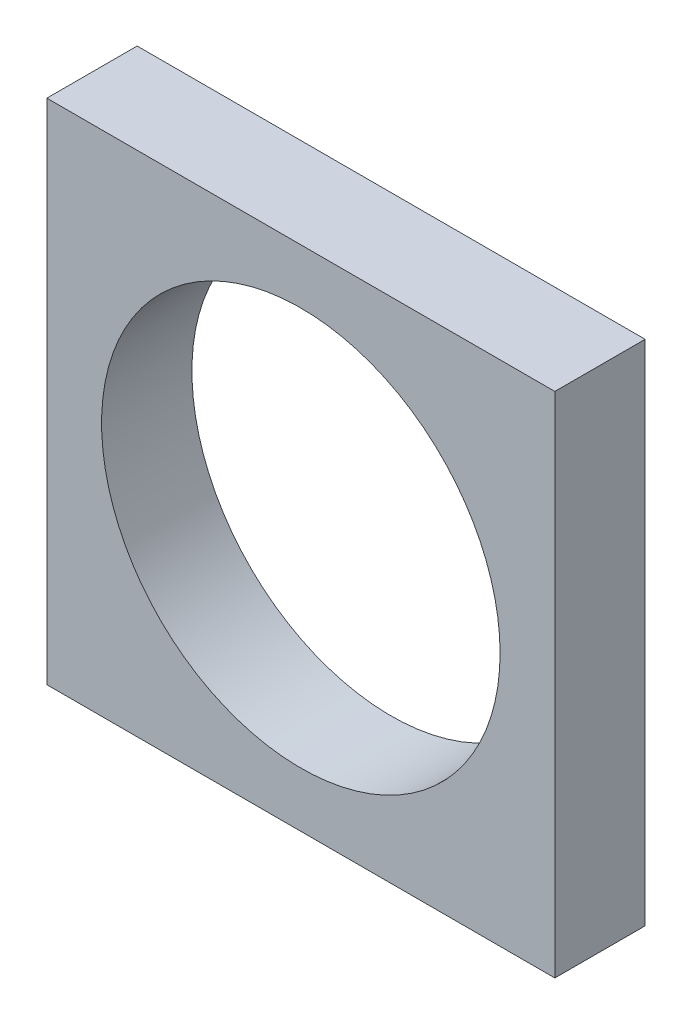
SolidWorks part; units mm, degrees
ref_plane "Front Plane" through (0, 0, 0) normal (0, 0, 1) x (1, 0, 0)
ref_plane "Top Plane" through (0, 0, 0) normal (0, 1, 0) x (1, 0, 0)
ref_plane "Right Plane" through (0, 0, 0) normal (1, 0, 0) x (0, 0, -1)
sketch "Sketch1" plane through (0, 0, 0) normal (0, 0, 1) x (1, 0, 0)
  line L1 (-22.5, -22.5) -> (22.5, -22.5)
  line L2 (-22.5, -22.5) -> (-22.5, 22.5)
  line L3 (-22.5, 22.5) -> (22.5, 22.5)
  line L4 (22.5, -22.5) -> (22.5, 22.5)
  line L5 (-22.5, -22.5) -> (22.5, 22.5) construction
  line L6 (-22.5, 22.5) -> (22.5, -22.5) construction
  circle A0 centre (0, 0) radius 17.65
  point P0 (0, 0)
  dimension "D3" = 35.3
  dimension "D1" = 45
  dimension "D2" = 45
extrude "Boss-Extrude1" add sketch "Sketch1" along normal blind 8
